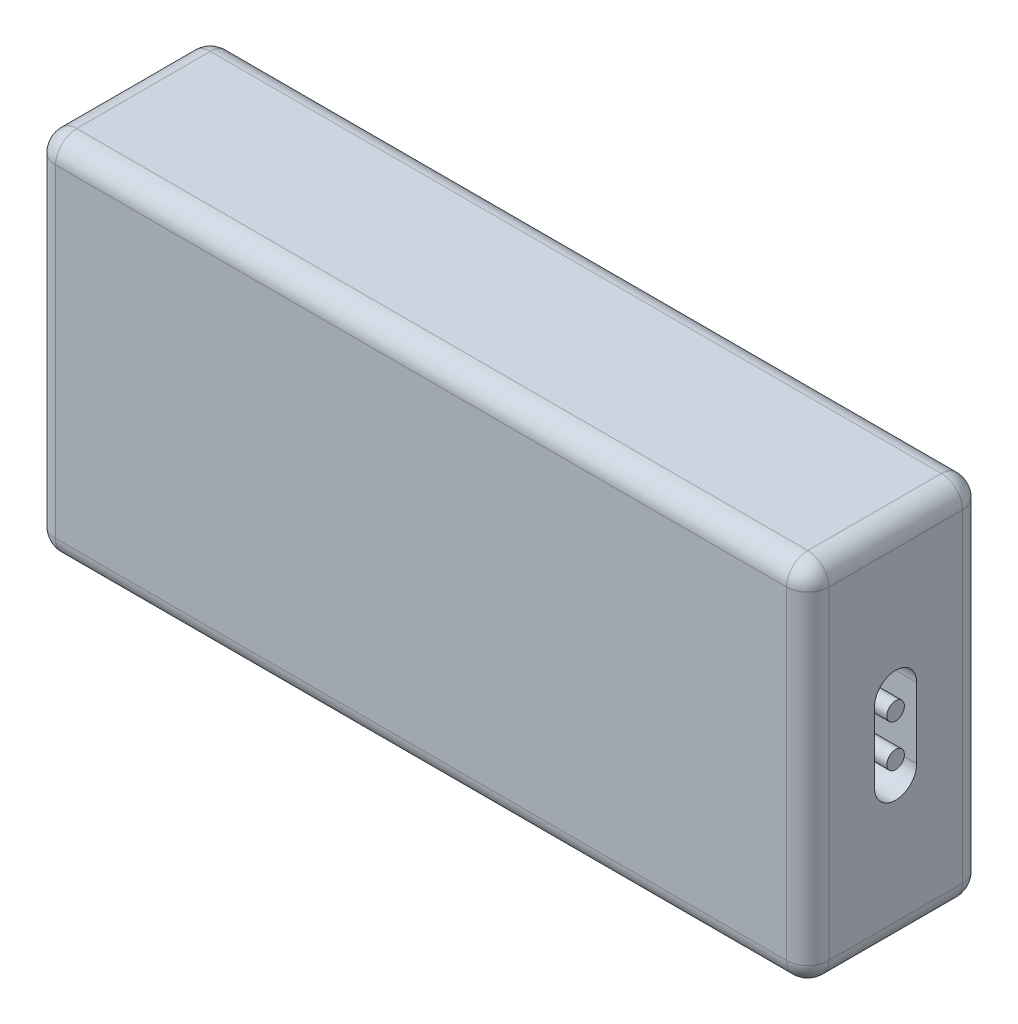
SolidWorks part; units mm, degrees
material "Резина"
ref_plane "Спереди" through (0, 0, 0) normal (0, 0, 1) x (1, 0, 0)
ref_plane "Сверху" through (0, 0, 0) normal (0, 1, 0) x (1, 0, 0)
ref_plane "Справа" through (0, 0, 0) normal (1, 0, 0) x (0, 0, -1)
sketch "Эскиз1" plane through (0, 0, 0) normal (0, 0, 1) x (1, 0, 0)
  line L0 (0, 0) -> (110, 0)
  line L1 (0, 0) -> (0, 52)
  line L2 (110, 0) -> (110, 52)
  line L3 (0, 52) -> (110, 52)
  dimension "D1" = 52
  dimension "D2" = 110
extrude "Бобышка-Вытянуть1" add sketch "Эскиз1" along normal blind 25
sketch "Эскиз2" plane through (110, 0, 0) normal (1, 0, 0) x (0, 0, -1)
  line L0 (-12.5, 0) -> (-12.5, 52) construction
  line L1 (-25, 0) -> (0, 0) construction
  line L2 (-25, 52) -> (0, 52) construction
  line L3 (0, 26) -> (-25, 26) construction
  line L4 (0, 0) -> (0, 52) construction
  line L5 (-25, 0) -> (-25, 52) construction
  line L6 (-12.5, 31) -> (-12.5, 21) construction
  line L7 (-9.5, 31) -> (-9.5, 21)
  line L8 (-15.5, 31) -> (-15.5, 21)
  arc A0 (-9.5, 31) -> (-15.5, 31) centre (-12.5, 31) ccw
  arc A1 (-15.5, 21) -> (-9.5, 21) centre (-12.5, 21) ccw
  circle A2 centre (-12.5, 29) radius 1.25
  circle A3 centre (-12.5, 23) radius 1.25
  point P14 (-12.5, 26)
  dimension "D3" = 2.5
  dimension "D4" = 3
  dimension "D5" = 3
  dimension "D1" = 6
  dimension "D2" = 10
extrude "Вырез-Вытянуть1" cut sketch "Эскиз2" against normal blind 6
sketch "Эскиз3" plane through (0, 0, 0) normal (-1, 0, 0) x (0, 0, 1)
  line L0 (12.5, 0) -> (12.5, 52) construction
  line L1 (25, 0) -> (0, 0) construction
  line L2 (25, 52) -> (0, 52) construction
  line L3 (0, 26) -> (25, 26) construction
  line L4 (0, 52) -> (0, 0) construction
  line L5 (25, 52) -> (25, 0) construction
  line L6 (10.5, 4) -> (14.5, 4)
  line L7 (10.5, 4) -> (10.5, 14)
  line L8 (14.5, 4) -> (14.5, 14)
  line L9 (10.5, 14) -> (14.5, 14)
  point P12 (12.5, 4)
  dimension "D1" = 10
  dimension "D2" = 4
  dimension "D3" = 4
extrude "Вырез-Вытянуть2" cut sketch "Эскиз3" against normal blind 6
sketch "Эскиз4" plane through (0, 0, 0) normal (-1, 0, 0) x (0, 0, 1)
  line L0 (0, 26) -> (25, 26) construction
  line L1 (0, 52) -> (0, 0) construction
  line L2 (25, 52) -> (25, 0) construction
  line L3 (12.5, 52) -> (12.5, 0) construction
  line L4 (25, 52) -> (0, 52) construction
  line L5 (25, 0) -> (0, 0) construction
  line L6 (10.5, 38) -> (14.5, 38)
  line L7 (10.5, 38) -> (10.5, 48)
  line L8 (14.5, 38) -> (14.5, 48)
  line L9 (10.5, 48) -> (14.5, 48)
  point P12 (12.5, 48)
  dimension "D1" = 10
  dimension "D2" = 4
  dimension "D3" = 4
extrude "Вырез-Вытянуть3" cut sketch "Эскиз4" against normal blind 6
sketch "Эскиз5" plane through (0, 0, 0) normal (0, 0, -1) x (-1, 0, 0)
  line L0 (-15, 5) -> (-32, 5)
  line L1 (-15, 5) -> (-15, 13)
  line L2 (-32, 5) -> (-32, 13)
  line L3 (-15, 13) -> (-32, 13)
  line L4 (0, 52) -> (0, 0) construction
  line L5 (0, 0) -> (-110, 0) construction
  dimension "D1" = 15
  dimension "D2" = 5
  dimension "D3" = 8
  dimension "D4" = 17
extrude "Вырез-Вытянуть4" cut sketch "Эскиз5" against normal blind 2
fillet "Скругление1" radius 3 12 edges at (0, 0, 12.5) (0, 52, 12.5) (0, 26, 25) (55, 0, 25) (110, 0, 12.5) (110, 26, 25) (110, 52, 12.5) (55, 52, 25) (0, 26, 0) (55, 0, 0) (110, 26, 0) (55, 52, 0)
sketch "Эскиз6" plane through (0, 0, 0) normal (0, 0, -1) x (-1, 0, 0)
  line L0 (-3, 26) -> (-107, 26) construction
  line L1 (-3, 3) -> (-3, 49) construction
  line L2 (-107, 49) -> (-107, 3) construction
ref_plane "SymPower" through (0, 26, 0) normal (0, 1, 0) x (1, 0, 0)
